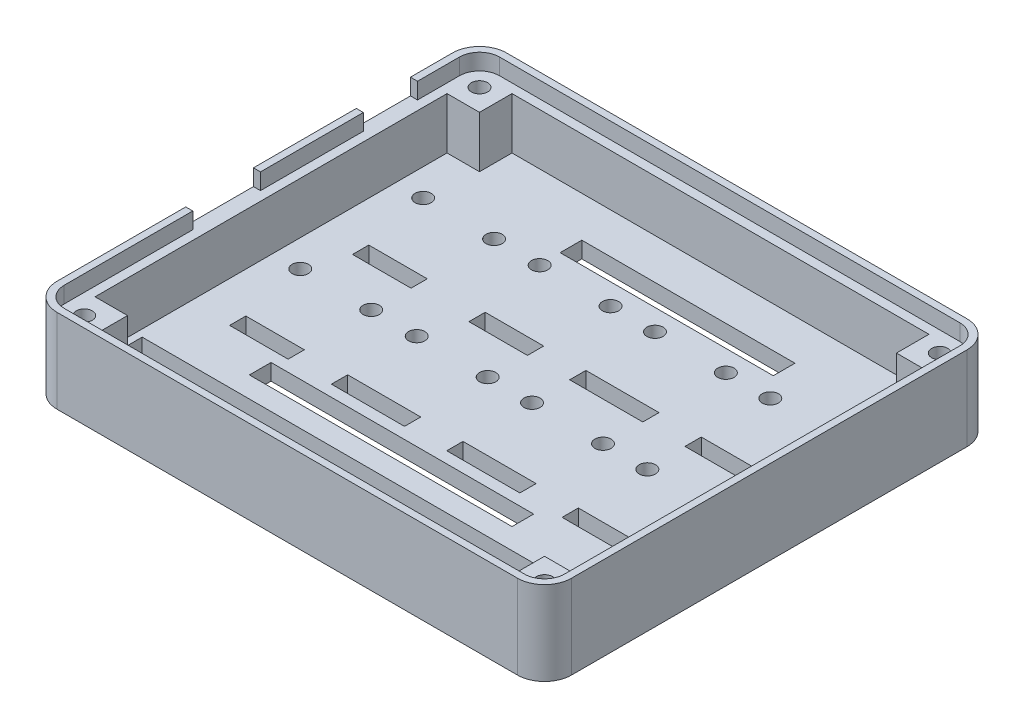
SolidWorks part; units mm, degrees
ref_plane "Front" through (0, 0, 0) normal (0, 0, 1) x (1, 0, 0)
ref_plane "Top" through (0, 0, 0) normal (0, 1, 0) x (1, 0, 0)
ref_plane "Right" through (0, 0, 0) normal (1, 0, 0) x (0, 0, -1)
sketch "Sketch1" plane through (0, 0, 0) normal (0, 1, 0) x (1, 0, 0)
  line L1 (0, 0) -> (95, 0)
  line L2 (0, 0) -> (0, 83)
  line L3 (0, 83) -> (95, 83)
  line L4 (95, 0) -> (95, 83)
  dimension "D1" = 83
  dimension "D2" = 95
extrude "Boss-Extrude1" add sketch "Sketch1" along normal blind 3
sketch "Sketch3" plane through (0, 3, 0) normal (0, 1, 0) x (1, 0, 0)
  line L5 (0, 83) -> (95, 83)
  line L6 (0, 83) -> (0, 0)
  line L7 (0, 0) -> (95, 0)
  line L8 (3, 80) -> (3, 3)
  line L9 (3, 3) -> (92, 3)
  line L10 (92, 3) -> (92, 80)
  line L11 (92, 80) -> (3, 80)
  line L12 (3, 80) -> (3, 3)
  line L13 (3, 3) -> (92, 3)
  line L14 (92, 3) -> (92, 80)
  line L15 (92, 80) -> (3, 80)
  line L16 (95, 83) -> (95, 0)
  dimension "D1" = 3
extrude "Boss-Extrude2" add sketch "Sketch3" along normal blind 9.5
sketch "Sketch4" plane through (0, 3, 0) normal (0, 1, 0) x (1, 0, 0)
  line L1 (3, 80) -> (9, 80)
  line L2 (3, 80) -> (3, 74)
  line L3 (3, 74) -> (9, 74)
  line L4 (9, 80) -> (9, 74)
  line L5 (3, 3) -> (9, 3)
  line L6 (3, 3) -> (3, 9)
  line L7 (3, 9) -> (9, 9)
  line L8 (9, 3) -> (9, 9)
  line L9 (92, 3) -> (86, 3)
  line L10 (92, 3) -> (92, 9)
  line L11 (92, 9) -> (86, 9)
  line L12 (86, 3) -> (86, 9)
  line L13 (92, 80) -> (86, 80)
  line L14 (92, 80) -> (92, 74)
  line L15 (92, 74) -> (86, 74)
  line L16 (86, 80) -> (86, 74)
  dimension "D1" = 6
  dimension "D2" = 6
  dimension "D3" = 6
  dimension "D4" = 6
extrude "Boss-Extrude3" add sketch "Sketch4" along normal up to surface (9.5 mm away) up to face at (47.5, 12.5, -41.5)
fillet "Fillet1" radius 5 4 edges at (95, 6.25, -83) (95, 6.25, 0) (0, 6.25, -83) (0, 6.25, 0)
sketch "Sketch5" plane through (0, 12.5, 0) normal (0, 1, 0) x (1, 0, 0)
  line L0 (9, 9) -> (3, 9) construction
  line L1 (9, 3) -> (9, 9) construction
  line L3 (86, 9) -> (86, 3) construction
  line L4 (92, 9) -> (86, 9) construction
  line L5 (86, 80) -> (86, 74) construction
  line L6 (86, 74) -> (92, 74) construction
  line L7 (3, 74) -> (9, 74) construction
  line L8 (9, 74) -> (9, 80) construction
  circle A0 centre (5, 78) radius 1.5
  circle A1 centre (90, 78) radius 1.5
  circle A2 centre (90, 5) radius 1.5
  circle A3 centre (5, 5) radius 1.5
  dimension "D1" = 3
  dimension "D4" = 3
  dimension "D7" = 3
  dimension "D10" = 3
  dimension "D2" = 4
  dimension "D3" = 4
  dimension "D5" = 4
  dimension "D6" = 4
  dimension "D8" = 4
  dimension "D9" = 4
  dimension "D11" = 4
  dimension "D12" = 4
extrude "Cut-Extrude1" cut sketch "Sketch5" against normal up to surface (12.5 mm away) up to face at (47.5, 0, -41.5)
sketch "Sketch6" plane through (0, 12.5, 0) normal (0, 1, 0) x (1, 0, 0)
  line L4 (5, 0) -> (90, 0)
  line L5 (95, 5) -> (95, 78)
  line L6 (90, 83) -> (5, 83)
  line L7 (0, 78) -> (0, 5)
  line L8 (5, 1.3) -> (90, 1.3)
  line L9 (93.7, 5) -> (93.7, 78)
  line L10 (90, 81.7) -> (5, 81.7)
  line L11 (1.3, 78) -> (1.3, 5)
  line L12 (5, 1.3) -> (90, 1.3)
  line L13 (93.7, 5) -> (93.7, 78)
  line L14 (90, 81.7) -> (5, 81.7)
  line L15 (1.3, 78) -> (1.3, 5)
  arc A4 (90, 0) -> (95, 5) centre (90, 5) ccw
  arc A5 (95, 78) -> (90, 83) centre (90, 78) ccw
  arc A6 (5, 83) -> (0, 78) centre (5, 78) ccw
  arc A7 (0, 5) -> (5, 0) centre (5, 5) ccw
  arc A8 (1.3, 5) -> (5, 1.3) centre (5, 5) ccw
  arc A9 (90, 1.3) -> (93.7, 5) centre (90, 5) ccw
  arc A10 (93.7, 78) -> (90, 81.7) centre (90, 78) ccw
  arc A11 (5, 81.7) -> (1.3, 78) centre (5, 78) ccw
  arc A12 (1.3, 5) -> (5, 1.3) centre (5, 5) ccw
  arc A13 (90, 1.3) -> (93.7, 5) centre (90, 5) ccw
  arc A14 (93.7, 78) -> (90, 81.7) centre (90, 78) ccw
  arc A15 (5, 81.7) -> (1.3, 78) centre (5, 78) ccw
  dimension "D1" = 1.3
  dimension "D2" = 1.3
extrude "Boss-Extrude4" add sketch "Sketch6" along normal blind 3
sketch "Sketch7" plane through (0, 0, 0) normal (-1, 0, 0) x (0, 0, 1)
  line L0 (-78, 15.5) -> (-5, 15.5) construction
  line L1 (-28.75, 15.5) -> (-41.25, 15.5)
  line L2 (-28.75, 15.5) -> (-28.75, 12.5)
  line L3 (-28.75, 12.5) -> (-41.25, 12.5)
  line L4 (-41.25, 15.5) -> (-41.25, 12.5)
  line L5 (-78, 12.5) -> (-5, 12.5) construction
  line L6 (-78, 15.5) -> (-78, 0) construction
  line L7 (-70.25, 15.5) -> (-60.25, 15.5)
  line L8 (-70.25, 15.5) -> (-70.25, 12.5)
  line L9 (-70.25, 12.5) -> (-60.25, 12.5)
  line L10 (-60.25, 15.5) -> (-60.25, 12.5)
  dimension "D1" = 7.75
  dimension "D2" = 12.5
  dimension "D3" = 10
  dimension "D4" = 19
extrude "Cut-Extrude2" cut sketch "Sketch7" against normal up to surface (1.3 mm away) up to face at (1.3, 14, -41.5)
sketch "Sketch8" plane through (0, 0, 0) normal (0, -1, 0) x (1, 0, 0)
  line L0 (0, -78) -> (0, -5) construction
  line L1 (4.3, -10.9) -> (90.3, -10.9)
  line L2 (4.3, -10.9) -> (4.3, -16.4)
  line L3 (4.3, -16.4) -> (90.3, -16.4)
  line L4 (90.3, -10.9) -> (90.3, -16.4)
  line L5 (5, 0) -> (90, 0) construction
  line L7 (20.25, -20.25) -> (68.75, -20.25)
  line L8 (20.25, -20.25) -> (20.25, -24.25)
  line L9 (20.25, -24.25) -> (68.75, -24.25)
  line L10 (68.75, -20.25) -> (68.75, -24.25)
  line L19 (68.75, -68.5) -> (29.39, -68.5)
  line L20 (68.75, -68.5) -> (68.75, -72.5)
  line L21 (68.75, -72.5) -> (29.39, -72.5)
  line L22 (29.39, -68.5) -> (29.39, -72.5)
  dimension "D1" = 4.3
  dimension "D2" = 5.5
  dimension "D3" = 86
  dimension "D4" = 10.9
  dimension "D5" = 20.25
  dimension "D6" = 4
  dimension "D7" = 4
  dimension "D8" = 15.25
  dimension "D9" = 48.5
  dimension "D10" = 9.14
  dimension "D11" = 44.25
extrude "Cut-Extrude3" cut sketch "Sketch8" against normal up to surface (3 mm away) up to face at (47.5, 3, -41.5)
sketch "Sketch10" plane through (0, 0, 0) normal (0, -1, 0) x (1, 0, 0)
  line L1 (10.5, -26.35) -> (21.3, -26.35)
  line L2 (10.5, -26.35) -> (10.5, -29.35)
  line L3 (10.5, -29.35) -> (21.3, -29.35)
  line L4 (21.3, -26.35) -> (21.3, -29.35)
  line L5 (29.3, -26.35) -> (42.8, -26.35)
  line L6 (29.3, -26.35) -> (29.3, -29.35)
  line L7 (29.3, -29.35) -> (42.8, -29.35)
  line L8 (42.8, -26.35) -> (42.8, -29.35)
  line L9 (50.6, -26.35) -> (64.1, -26.35)
  line L10 (50.6, -26.35) -> (50.6, -29.35)
  line L11 (50.6, -29.35) -> (64.1, -29.35)
  line L12 (64.1, -26.35) -> (64.1, -29.35)
  line L13 (71.9, -26.35) -> (85.4, -26.35)
  line L14 (71.9, -26.35) -> (71.9, -29.35)
  line L15 (71.9, -29.35) -> (85.4, -29.35)
  line L16 (85.4, -26.35) -> (85.4, -29.35)
  line L17 (10.5, -49.05) -> (21.3, -49.05)
  line L18 (10.5, -49.05) -> (10.5, -52.05)
  line L19 (10.5, -52.05) -> (21.3, -52.05)
  line L20 (21.3, -49.05) -> (21.3, -52.05)
  line L21 (32, -49.05) -> (42.8, -49.05)
  line L22 (32, -49.05) -> (32, -52.05)
  line L23 (32, -52.05) -> (42.8, -52.05)
  line L24 (42.8, -49.05) -> (42.8, -52.05)
  line L25 (50.6, -49.05) -> (64.1, -49.05)
  line L26 (50.6, -49.05) -> (50.6, -52.05)
  line L27 (50.6, -52.05) -> (64.1, -52.05)
  line L28 (64.1, -49.05) -> (64.1, -52.05)
  line L29 (71.9, -49.05) -> (85.4, -49.05)
  line L30 (71.9, -49.05) -> (71.9, -52.05)
  line L31 (71.9, -52.05) -> (85.4, -52.05)
  line L32 (85.4, -49.05) -> (85.4, -52.05)
  dimension "D1" = 13.5
  dimension "D2" = 13.5
  dimension "D3" = 13.5
  dimension "D4" = 3
  dimension "D5" = 3
  dimension "D6" = 21.35
  dimension "D7" = 10.8
  dimension "D8" = 10.8
  dimension "D9" = 10.5
  dimension "D10" = 19.7
  dimension "D11" = 10.7
  dimension "D12" = 7.8
  dimension "D13" = 7.8
extrude "Cut-Extrude4" cut sketch "Sketch10" against normal up to surface (3 mm away) up to face at (44.5, 3, -22.25)
sketch "Sketch11" plane through (0, 0, 0) normal (0, -1, 0) x (1, 0, 0)
  line L0 (10.5, -26.35) -> (10.5, -29.35) construction
  line L1 (10.5, -49.05) -> (10.5, -52.05) construction
  line L3 (29.3, -29.35) -> (42.8, -29.35) construction
  line L4 (50.6, -29.35) -> (64.1, -29.35) construction
  line L5 (71.9, -29.35) -> (85.4, -29.35) construction
  line L6 (10.5, -29.35) -> (21.3, -29.35) construction
  circle A0 centre (8, -41.9) radius 1.5
  circle A1 centre (21.1, -41.9) radius 1.5
  circle A2 centre (29.5, -41.9) radius 1.5
  circle A3 centre (42.6, -41.9) radius 1.5
  circle A4 centre (50.8, -41.9) radius 1.5
  circle A5 centre (63.9, -41.9) radius 1.5
  circle A6 centre (72.1, -41.9) radius 1.5
  circle A7 centre (85.2, -41.9) radius 1.5
  circle A8 centre (85.2, -64.6) radius 1.5
  circle A9 centre (72.1, -64.6) radius 1.5
  circle A10 centre (63.9, -64.6) radius 1.5
  circle A11 centre (50.8, -64.6) radius 1.5
  circle A12 centre (42.6, -64.6) radius 1.5
  circle A13 centre (29.5, -64.6) radius 1.5
  circle A14 centre (21.1, -64.6) radius 1.5
  circle A15 centre (8, -64.6) radius 1.5
  point P32 (0, 0)
  point P33 (0, 0)
  point P34 (0, 0)
  point P35 (0, 0)
  point P36 (0, 0)
  point P37 (0, 0)
  point P38 (0, 0)
  point P39 (0, 0)
  point P40 (0, 0)
  point P41 (0, 0)
  point P44 (10.5, -27.85)
  point P47 (10.5, -50.55)
  point P48 (8.5675, -41.9)
  point P49 (0, 0)
  point P52 (0, 0)
  point P55 (36.05, -29.35)
  point P58 (57.35, -29.35)
  point P61 (78.65, -29.35)
  point P62 (15.9, -29.35)
  dimension "D1" = 3
  dimension "D2" = 3
  dimension "D3" = 3
  dimension "D4" = 3
  dimension "D5" = 3
  dimension "D6" = 3
  dimension "D7" = 3
  dimension "D8" = 3
  dimension "D9" = 3
  dimension "D10" = 3
  dimension "D11" = 3
  dimension "D12" = 3
  dimension "D13" = 3
  dimension "D14" = 3
  dimension "D15" = 3
  dimension "D16" = 3
  dimension "D17" = 13.1
  dimension "D18" = 13.1
  dimension "D19" = 13.1
  dimension "D20" = 13.1
  dimension "D21" = 14.05
  dimension "D22" = 14.05
  dimension "D23" = 5.2
  dimension "D24" = 6.55
  dimension "D25" = 6.55
  dimension "D26" = 6.55
extrude "Cut-Extrude5" cut sketch "Sketch11" against normal up to surface (3 mm away) up to face at (36.05, 3, -27.85)
